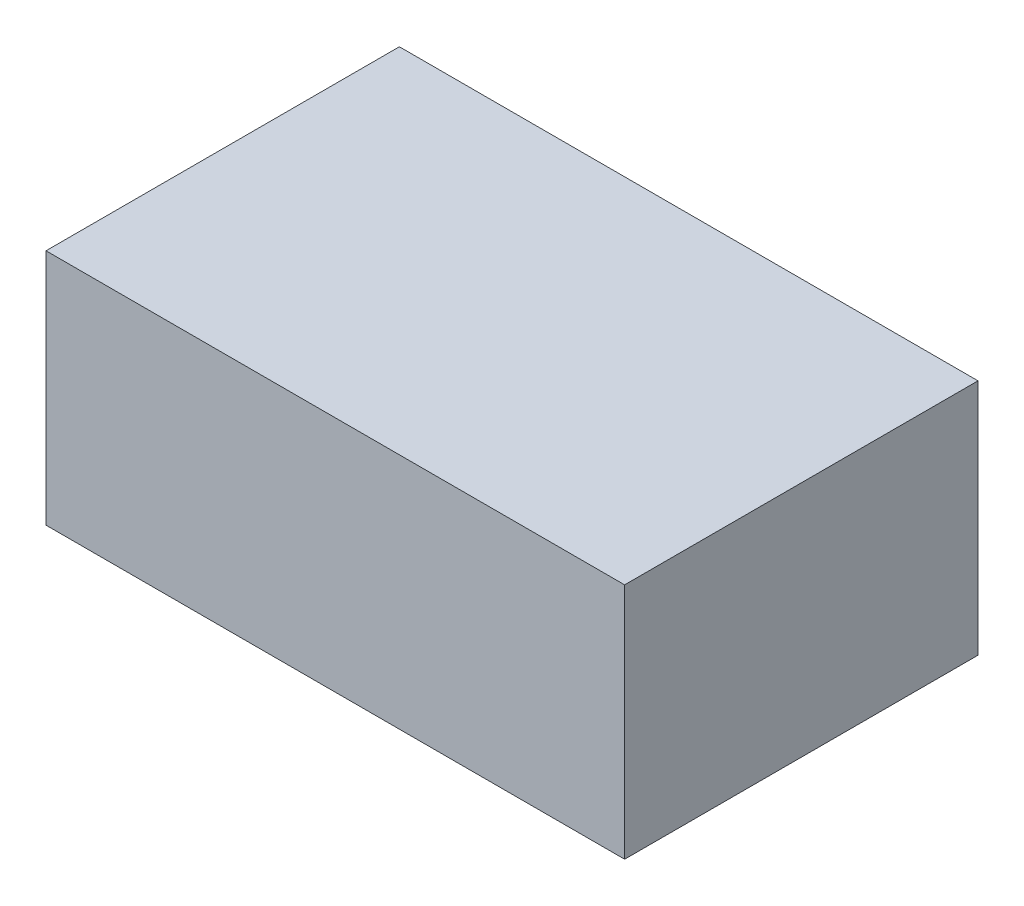
SolidWorks part; units mm, degrees
ref_plane "Front Plane" through (0, 0, 0) normal (0, 0, 1) x (1, 0, 0)
ref_plane "Top Plane" through (0, 0, 0) normal (0, 1, 0) x (1, 0, 0)
ref_plane "Right Plane" through (0, 0, 0) normal (1, 0, 0) x (0, 0, -1)
sketch "Sketch1" plane through (0, 0, 0) normal (0, 0, 1) x (1, 0, 0)
  line L4 (-1.17, 0.22) -> (-1.17, -0.24)
  line L5 (-1.17, -0.24) -> (-0.05, -0.24)
  line L6 (-0.05, -0.24) -> (-0.05, 0.22)
  line L7 (-0.05, 0.22) -> (-1.17, 0.22)
  line L8 (-1.17, 0.22) -> (-1.17, -0.24)
  line L9 (-1.17, -0.24) -> (-0.05, -0.24)
  line L10 (-0.05, -0.24) -> (-0.05, 0.22)
  line L11 (-0.05, 0.22) -> (-1.17, 0.22)
  dimension "D1" = 0
extrude "Boss-Extrude1" add sketch "Sketch1" against normal up to surface (0.684 mm away)
